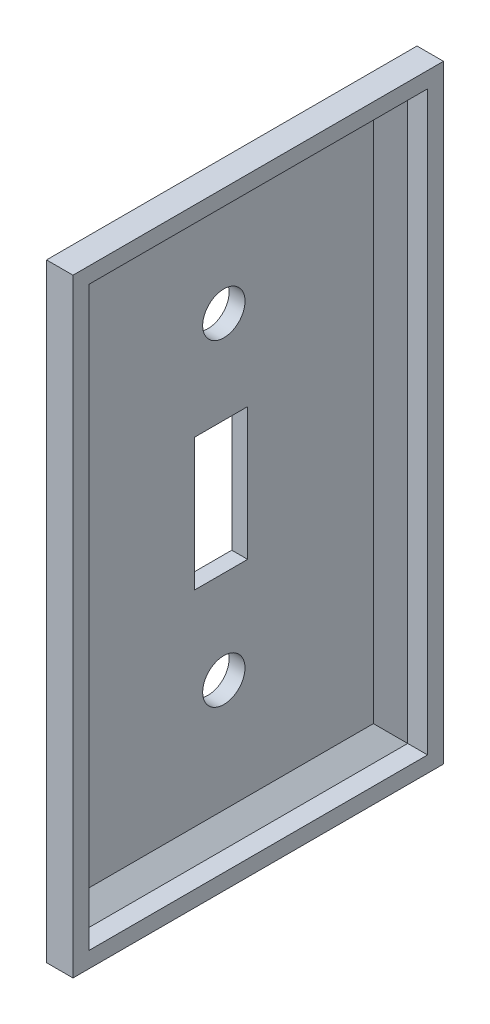
SolidWorks part; units mm, degrees
ref_plane "Alzado" through (0, 0, 0) normal (0, 0, 1) x (1, 0, 0)
ref_plane "Planta" through (0, 0, 0) normal (0, 1, 0) x (1, 0, 0)
ref_plane "Vista lateral" through (0, 0, 0) normal (1, 0, 0) x (0, 0, -1)
sketch "Croquis1" plane through (0, 0, 0) normal (1, 0, 0) x (0, 0, -1)
  line L1 (0, 0) -> (70, 0)
  line L2 (0, 0) -> (0, 115)
  line L3 (0, 115) -> (70, 115)
  line L4 (70, 0) -> (70, 115)
  dimension "D1" = 70
  dimension "D2" = 115
extrude "Saliente-Extruir1" add sketch "Croquis1" along normal blind 10
chamfer "Chaflán2" distance 5 angle 45 4 edges at (0, 0, -35) (0, 57.5, -70) (0, 115, -35) (0, 57.5, 0)
shell "Vaciado1" thickness 3
sketch "Croquis5" plane through (3, 0, 0) normal (1, 0, 0) x (0, 0, -1)
  line L0 (0, 115) -> (0, 0) construction
  line L1 (30, 70) -> (40, 70)
  line L2 (30, 70) -> (30, 45)
  line L3 (30, 45) -> (40, 45)
  line L4 (40, 70) -> (40, 45)
  line L6 (0, 0) -> (70, 0) construction
  circle A0 centre (35.5, 87.5) radius 4
  circle A1 centre (35.5, 27.5) radius 4
  dimension "D5" = 8
  dimension "D6" = 8
  dimension "D1" = 25
  dimension "D2" = 10
  dimension "D3" = 30
  dimension "D4" = 45
  dimension "D7" = 27.5
  dimension "D8" = 35.5
  dimension "D9" = 60
  dimension "D10" = 35.5
extrude "Cortar-Extruir1" cut sketch "Croquis5" against normal through all
